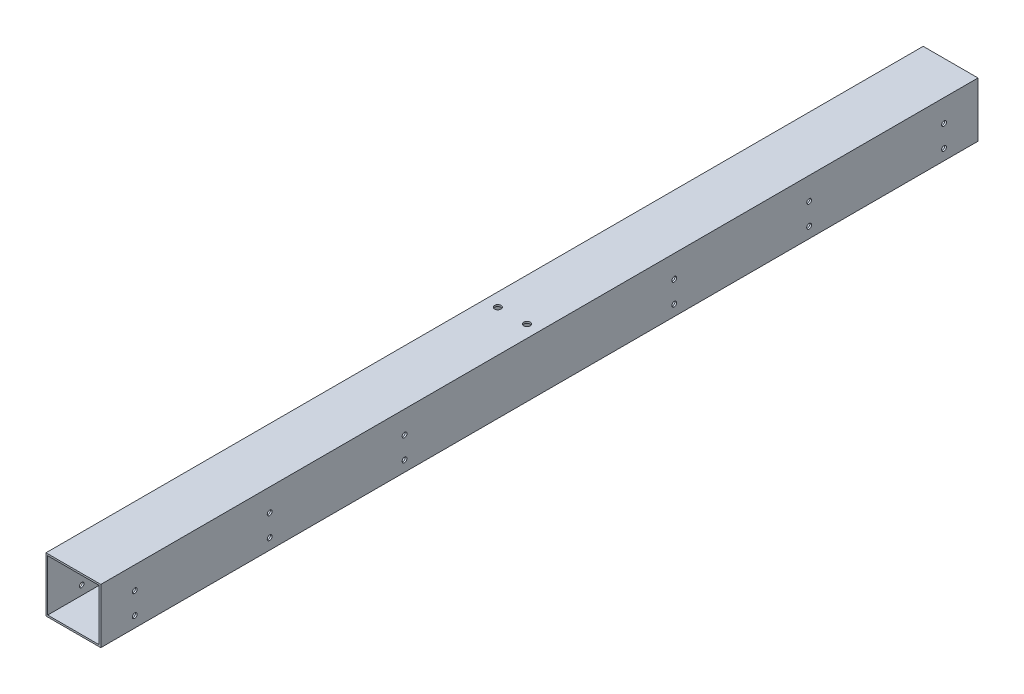
SolidWorks part; units mm, degrees
material "6063-T6"
ref_plane "Front Plane" through (0, 0, 0) normal (0, 0, 1) x (1, 0, 0)
ref_plane "Top Plane" through (0, 0, 0) normal (0, 1, 0) x (1, 0, 0)
ref_plane "Right Plane" through (0, 0, 0) normal (1, 0, 0) x (0, 0, -1)
sketch "Sketch1" plane through (0, 0, 0) normal (0, 0, 1) x (1, 0, 0)
  line L1 (-50.8, 50.8) -> (50.8, 50.8)
  line L2 (-50.8, 50.8) -> (-50.8, -50.8)
  line L3 (-50.8, -50.8) -> (50.8, -50.8)
  line L4 (50.8, 50.8) -> (50.8, -50.8)
  line L5 (-50.8, 50.8) -> (50.8, -50.8) construction
  line L6 (-50.8, -50.8) -> (50.8, 50.8) construction
  point P0 (0, 0)
  dimension "D1" = 101.6
extrude "Extrude-Thin1" add sketch "Sketch1" along normal mid plane 1626 thin
hole_wizard "M8 Clearance Hole2" positions "Sketch2" profile "Sketch3" hole size "M8" standard "ANSI Metric"
sketch "Sketch2" plane through (-50.8, 0, 0) normal (-1, 0, 0) x (0, 0, 1)
  line L0 (750, 9.2) -> (750, -30.8)
  line L1 (750, -30.8) -> (750, -50.8)
  line L2 (813, -50.8) -> (-813, -50.8) construction
  point P0 (750, 9.2)
  point P2 (750, -30.8)
  dimension "D1" = 40
  dimension "D2" = 20
  dimension "D3" = 750
sketch "Sketch3" plane through (-50.8, 9.2, 750) normal (0, 1, 0) x (0, 0, 1)
  line L0 (0, 0) -> (0, 3.175)
  line L1 (0, 3.175) -> (4.2, 3.175)
  line L2 (4.2, 3.175) -> (4.2, 0)
  line L5 (4.2, 0) -> (0, 0)
  line L11 (0, -6.35) -> (0, 107.95) construction
  dimension "Thru Hole Dia." = 8.4
  dimension "Thru Hole Depth" = 3.175
hole_wizard "M8 Clearance Hole1" positions "Sketch4" profile "Sketch5" hole size "M8" standard "ANSI Metric"
sketch "Sketch4" plane through (47.625, 0, 0) normal (-1, 0, 0) x (0, 0, 1)
  point P0 (750, 9.2)
  point P3 (750, -30.8)
sketch "Sketch5" plane through (47.625, 9.2, 750) normal (0, 1, 0) x (0, 0, 1)
  line L0 (0, 0) -> (0, 3.175)
  line L1 (0, 3.175) -> (4.5, 3.175)
  line L2 (4.5, 3.175) -> (4.5, 0)
  line L5 (4.5, 0) -> (0, 0)
  line L11 (0, -6.35) -> (0, 107.95) construction
  dimension "Thru Hole Dia." = 9
  dimension "Thru Hole Depth" = 3.175
pattern_linear "LPattern1" count 7 spacing 250 along (0, 0, -1) skipping (3, 0) of "M8 Clearance Hole2", "M8 Clearance Hole1"
hole_wizard "Ø12.0 (12) Diameter Hole1" positions "Sketch6" profile "Sketch7" hole size "Ø12.0" standard "ANSI Metric"
sketch "Sketch6" plane through (0, 50.8, 0) normal (0, 1, 0) x (1, 0, 0)
  line L0 (27.8, 0) -> (-26.2, 0)
  line L2 (50.8, -813) -> (50.8, 813) construction
  point P0 (-26.2, 0)
  point P2 (27.8, 0)
  point P13 (0.8, 0)
  dimension "D1" = 54
  dimension "D2" = 50
  dimension "D3" = 0
sketch "Sketch7" plane through (-26.2, 50.8, 0) normal (1, 0, 0) x (0, 0, 1)
  line L0 (0, 0) -> (0, 3.175)
  line L1 (0, 3.175) -> (6, 3.175)
  line L2 (6, 3.175) -> (6, 0)
  line L5 (6, 0) -> (0, 0)
  line L11 (0, -6.35) -> (0, 107.95) construction
  dimension "Thru Hole Dia." = 12
  dimension "Thru Hole Depth" = 3.175
